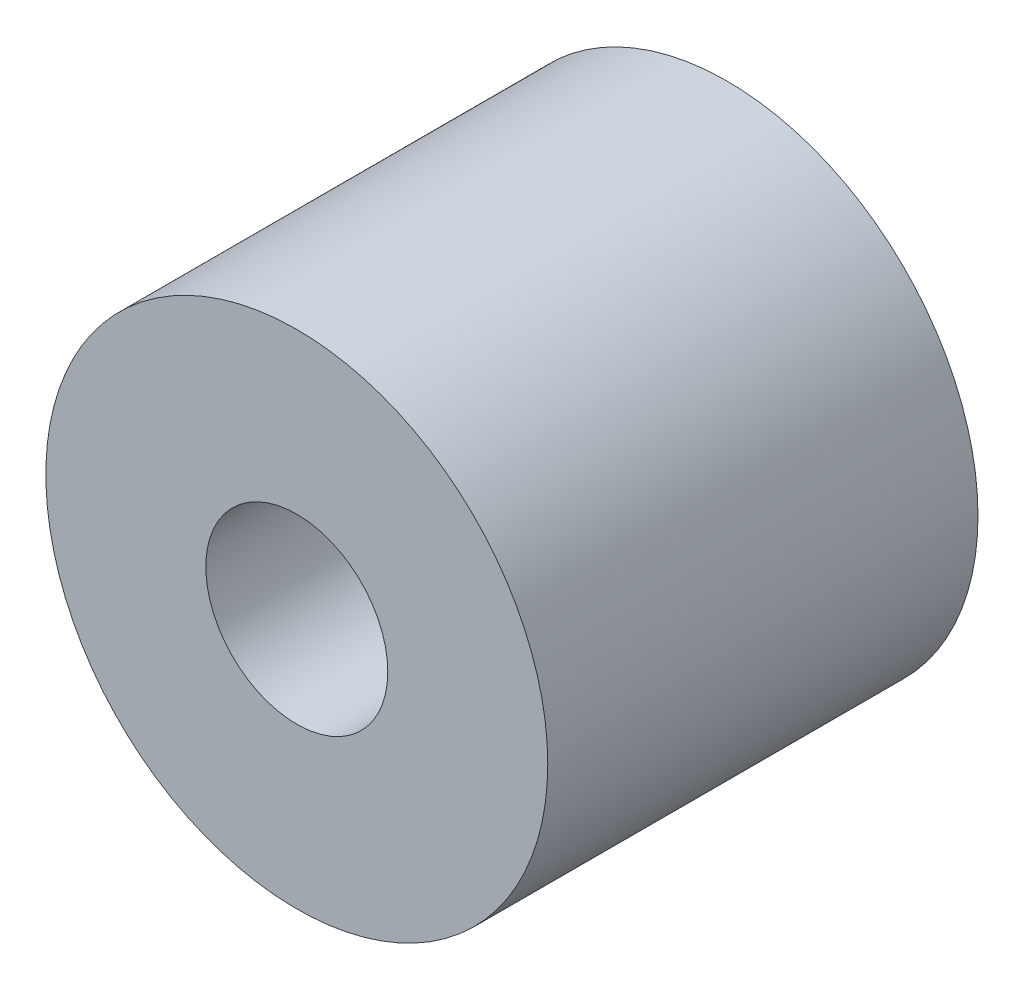
SolidWorks part; units mm, degrees
ref_plane "Front Plane" through (0, 0, 0) normal (0, 0, 1) x (1, 0, 0)
ref_plane "Top Plane" through (0, 0, 0) normal (0, 1, 0) x (1, 0, 0)
ref_plane "Right Plane" through (0, 0, 0) normal (1, 0, 0) x (0, 0, -1)
sketch "Sketch1" plane through (0, 0, 0) normal (0, 0, 1) x (1, 0, 0)
  circle A0 centre (0, 0) radius 17.5
  circle A1 centre (0, 0) radius 6.345
  dimension "D1" = 35
  dimension "D2" = 12.69
extrude "Boss-Extrude1" add sketch "Sketch1" along normal blind 30
sketch "Sketch2" plane through (0, 0, 0) normal (0, 1, 0) x (1, 0, 0)
  line L0 (0, 0) -> (0, -30) construction
  line L1 (-17.5, -30) -> (17.5, -30) construction
